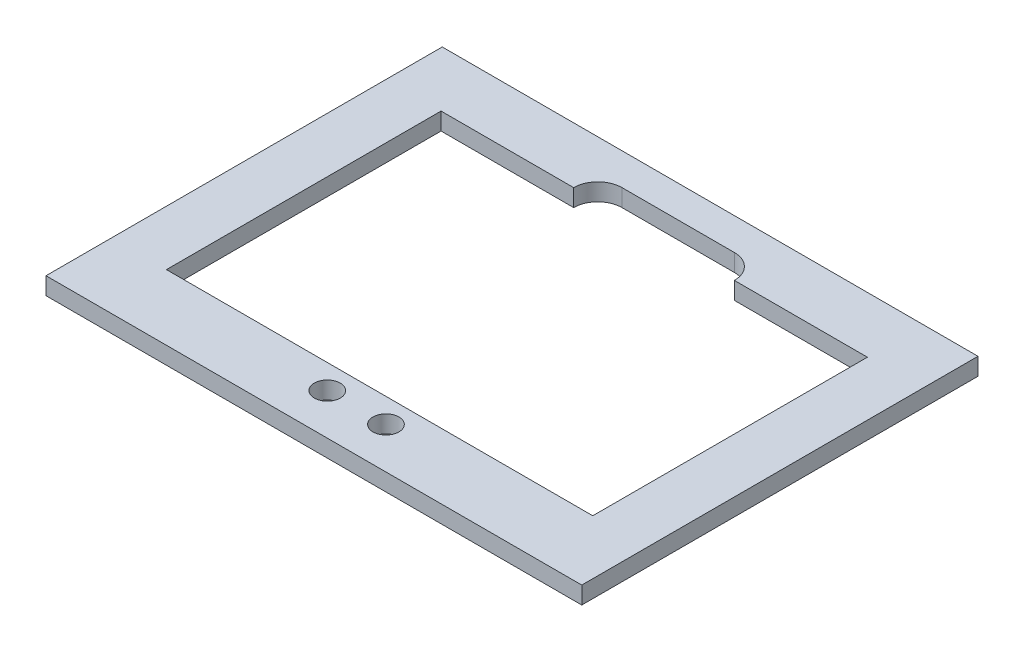
SolidWorks part; units mm, degrees
ref_plane "Front Plane" through (0, 0, 0) normal (0, 0, 1) x (1, 0, 0)
ref_plane "Top Plane" through (0, 0, 0) normal (0, 1, 0) x (1, 0, 0)
ref_plane "Right Plane" through (0, 0, 0) normal (1, 0, 0) x (0, 0, -1)
sketch "Sketch1" plane through (0, 0, 0) normal (0, 1, 0) x (1, 0, 0)
  line L28 (-39.5941, 29.2447) -> (38.9359, 29.2447)
  line L37 (-39.5941, 29.2447) -> (-39.5941, -28.8353)
  line L38 (-39.5941, -28.8353) -> (38.9359, -28.8353)
  line L39 (38.9359, 29.2447) -> (38.9359, -28.8353)
  line L40 (-31.5441, 21.0211) -> (30.9476, 21.0211)
  line L41 (-31.5441, 21.0211) -> (-31.5441, -19.2326)
  line L42 (-31.5441, -19.2326) -> (30.9476, -19.2326)
  line L43 (30.9476, 21.0211) -> (30.9476, -19.2326)
  circle A8 centre (-4.4022, -22.7972) radius 1.905
  circle A9 centre (4.1978, -22.7972) radius 1.905
  point P12 (0, 0)
  point P13 (0, 0)
  dimension "D1" = 3.81
extrude "Boss-Extrude1" add sketch "Sketch1" along normal blind 2.54
sketch "Sketch2" plane through (0, 2.54, 0) normal (0, 1, 0) x (1, 0, 0)
  line L0 (-8.5687, 21.0211) -> (7.9104, 21.0211) construction
  line L1 (30.9476, 21.0211) -> (-31.5441, 21.0211) construction
  line L2 (-8.5687, 24.5643) -> (7.9104, 24.5643)
  line L3 (-8.5687, 17.4779) -> (7.9104, 17.4779)
  line L4 (38.9359, 29.2447) -> (-39.5941, 29.2447) construction
  arc A0 (-8.5687, 24.5643) -> (-8.5687, 17.4779) centre (-8.5687, 21.0211) ccw
  arc A1 (7.9104, 17.4779) -> (7.9104, 24.5643) centre (7.9104, 21.0211) ccw
  point P4 (-0.3291, 21.0211)
  point P12 (-0.3291, 29.2447)
extrude "Cut-Extrude1" cut sketch "Sketch2" against normal blind 2.54
